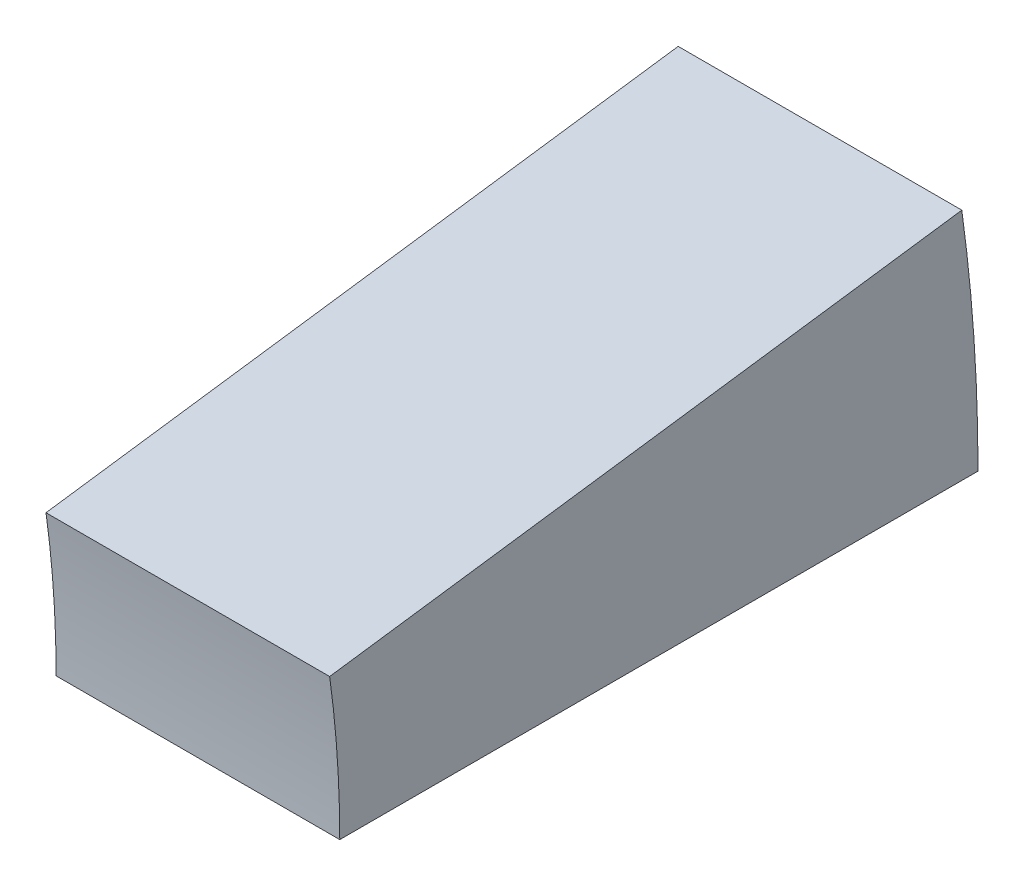
SolidWorks part; units mm, degrees
ref_plane "Alzado" through (0, 0, 0) normal (0, 0, 1) x (1, 0, 0)
ref_plane "Planta" through (0, 0, 0) normal (0, 1, 0) x (1, 0, 0)
ref_plane "Vista lateral" through (0, 0, 0) normal (1, 0, 0) x (0, 0, -1)
sketch "Croquis1" plane through (0, 0, 0) normal (0, 1, 0) x (1, 0, 0)
  line L1 (0, 0) -> (24, 0)
  line L2 (0, 0) -> (0, 144)
  line L3 (0, 144) -> (24, 144)
  line L4 (24, 0) -> (24, 144)
  dimension "D1" = 144
  dimension "D2" = 24
extrude "Saliente-Extruir1" add sketch "Croquis1" along normal blind 20
sketch "Croquis3" plane through (24, 0, 0) normal (1, 0, 0) x (0, 0, -1)
  line L0 (144, 20) -> (0, 0)
  line L1 (0, 0) -> (0, 20)
  line L2 (0, 20) -> (144, 20)
extrude "Cortar-Extruir2" cut sketch "Croquis3" against normal through all
sketch "Croquis6" plane through (0, 0, 0) normal (0, -1, 0) x (1, 0, 0)
  line L1 (24, -144) -> (0, -144)
sketch "Croquis7" plane through (0, 0, 0) normal (0, -1, 0) x (1, 0, 0)
  line L1 (24, -144) -> (0, -144)
  line L2 (24, -144) -> (24, -184.2614)
  line L3 (24, -184.2614) -> (0, -184.2614)
  line L4 (0, -144) -> (0, -184.2614)
revolve "Cortar-Revolución5" cut sketch "Croquis7" angle 360 about axis through (0, 0, 0) along (1, 0, 0)
sketch "Croquis4" plane through (0, 0, 0) normal (0, -1, 0) x (1, 0, 0)
  line L1 (24, 0) -> (24, -144) construction
  line L2 (24, -90) -> (0, -90)
  line L3 (24, -90) -> (24, 0)
  line L4 (24, 0) -> (0, 0)
  line L6 (0, -90) -> (0, 0)
  dimension "D1" = 90
revolve "Cortar-Revolución3" cut sketch "Croquis4" angle 360 about L4
